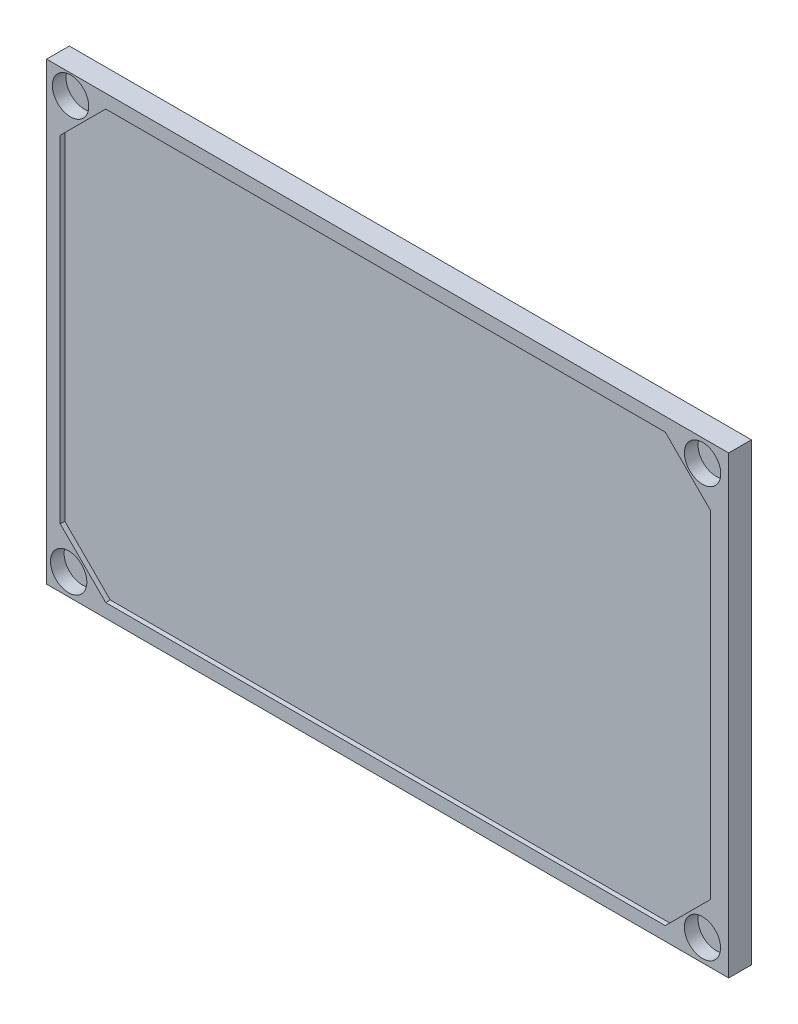
SolidWorks part; units mm, degrees
ref_plane "Plan de face" through (0, 0, 0) normal (0, 0, 1) x (1, 0, 0)
ref_plane "Plan de dessus" through (0, 0, 0) normal (0, 1, 0) x (1, 0, 0)
ref_plane "Plan de droite" through (0, 0, 0) normal (1, 0, 0) x (0, 0, -1)
sketch "Esquisse1" plane through (0, 0, 0) normal (0, 0, 1) x (1, 0, 0)
  line L1 (-96.1737, 39.2273) -> (53.8263, 39.2273)
  line L2 (-96.1737, 39.2273) -> (-96.1737, -60.7727)
  line L3 (-96.1737, -60.7727) -> (53.8263, -60.7727)
  line L4 (53.8263, 39.2273) -> (53.8263, -60.7727)
  dimension "D1" = 150
  dimension "D2" = 100
extrude "Boss.-Extru.1" add sketch "Esquisse1" along normal blind 5
sketch "Esquisse2" plane through (0, 0, 5) normal (0, 0, 1) x (1, 0, 0)
  line L0 (-96.1737, 39.2273) -> (-96.1737, -60.7727) construction
  line L1 (-83.1737, 36.2273) -> (39.8737, 36.2273)
  line L2 (-93.1737, 26.2273) -> (-93.1737, -47.7727)
  line L3 (-83.1737, -57.7727) -> (39.8737, -57.7727)
  line L4 (49.8737, 26.2273) -> (49.8737, -47.7727)
  line L5 (53.8263, 39.2273) -> (-96.1737, 39.2273) construction
  line L6 (53.8263, -60.7727) -> (53.8263, 39.2273) construction
  line L7 (-96.1737, -60.7727) -> (53.8263, -60.7727) construction
  line L8 (-83.1737, 36.2273) -> (-93.1737, 26.2273)
  line L9 (-93.1737, -47.7727) -> (-83.1737, -57.7727)
  line L10 (49.8737, -47.7727) -> (39.8737, -57.7727)
  line L11 (39.8737, 36.2273) -> (49.8737, 26.2273)
  point P0 (-93.1737, 36.2273)
  point P1 (49.8737, -57.7727)
  point P2 (-93.1737, -57.7727)
  point P3 (49.8737, 36.2273)
  dimension "D1" = 3
  dimension "D2" = 3
  dimension "D3" = 3.9526
  dimension "D4" = 3
extrude "Enlèv. mat.-Extru.1" cut sketch "Esquisse2" against normal blind 1
sketch "Esquisse3" plane through (0, 0, 5) normal (0, 0, 1) x (1, 0, 0)
  line L0 (-83.1737, 36.2273) -> (-93.1737, 26.2273) construction
  circle A0 centre (-90.9074, 34.8576) radius 4
  point P0 (-93.0653, 35.1934)
  point P1 (-87.729, 31.6721)
extrude "Enlèv. mat.-Extru.2" cut sketch "Esquisse3" against normal blind 3 contours A0
sketch "Esquisse6" plane through (0, 0, 5) normal (0, 0, 1) x (1, 0, 0)
  line L0 (49.8737, 26.2273) -> (39.8737, 36.2273) construction
  circle A0 centre (48.0833, 34.3814) radius 4
  point P0 (44.8737, 31.2273)
extrude "Enlèv. mat.-Extru.6" cut sketch "Esquisse6" against normal blind 3 contours A0
sketch "Esquisse7" plane through (0, 0, 5) normal (0, 0, 1) x (1, 0, 0)
  circle A0 centre (-91.323, -55.987) radius 4
extrude "Enlèv. mat.-Extru.8" cut sketch "Esquisse7" against normal blind 3 contours A0
sketch "Esquisse8" plane through (0, 0, 5) normal (0, 0, 1) x (1, 0, 0)
  line L0 (39.8737, -57.7727) -> (49.8737, -47.7727) construction
  circle A0 centre (48.0631, -55.9472) radius 3.9822
  point P0 (44.8744, -52.7719)
extrude "Enlèv. mat.-Extru.10" cut sketch "Esquisse8" against normal blind 3 contours A0
ref_plane "Plan8" [suppressed] through (-96.1737, 39.2273, 5) normal (0, 0, -1) x (-1, 0, 0)
